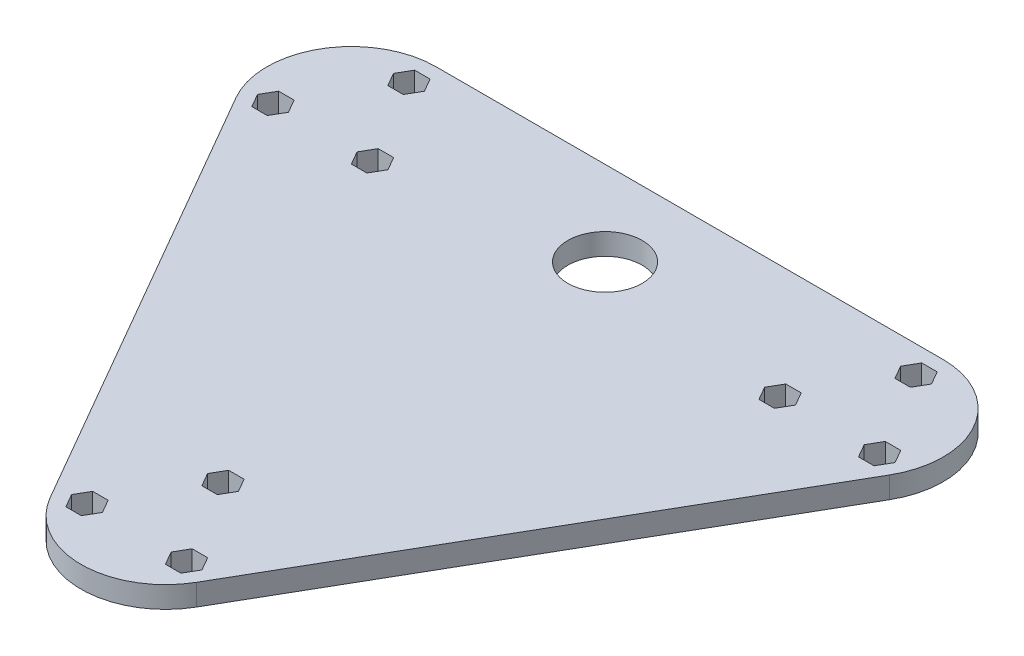
SolidWorks part; units mm, degrees
ref_plane "Plan de face" through (0, 0, 0) normal (0, 0, 1) x (1, 0, 0)
ref_plane "Plan de dessus" through (0, 0, 0) normal (0, 1, 0) x (1, 0, 0)
ref_plane "Plan de droite" through (0, 0, 0) normal (1, 0, 0) x (0, 0, -1)
sketch "Esquisse1" plane through (0, 0, 0) normal (0, 1, 0) x (1, 0, 0)
  line L0 (-96.6546, 52.5069) -> (-21.6546, -77.4931)
  line L1 (96.6546, 52.5069) -> (21.6546, -77.4931)
  line L2 (-75, 90) -> (75, 90)
  line L3 (-75, 65) -> (75, 65) construction
  arc A3 (-75, 90) -> (-96.6546, 52.5069) centre (-75, 65) ccw
  arc A4 (96.6546, 52.5069) -> (75, 90) centre (75, 65) ccw
  arc A5 (-21.6546, -77.4931) -> (21.6546, -77.4931) centre (0, -65) ccw
  circle A6 centre (0, 65) radius 11
  dimension "D1" = 22
  dimension "D6" = 50
  dimension "D2" = 65
  dimension "D3" = 65
  dimension "D4" = 150
  dimension "D5" = 75
extrude "Boss.-Extru.1" add sketch "Esquisse1" along normal blind 6.35
sketch "Esquisse3" plane through (0, 0, 0) normal (0, -1, 0) x (1, 0, 0)
  line L0 (75, -90) -> (-75, -90) construction
  line L1 (-79.5726, -82) -> (-77.2863, -85.96)
  line L2 (-77.2863, -85.96) -> (-72.7137, -85.96)
  line L3 (-72.7137, -85.96) -> (-70.4274, -82)
  line L4 (-70.4274, -82) -> (-72.7137, -78.04)
  line L5 (-72.7137, -78.04) -> (-77.2863, -78.04)
  line L6 (-77.2863, -78.04) -> (-79.5726, -82)
  line L7 (-94.295, -56.5) -> (-92.0087, -60.46)
  line L8 (-92.0087, -60.46) -> (-87.4361, -60.46)
  line L9 (-87.4361, -60.46) -> (-85.1498, -56.5)
  line L10 (-85.1498, -56.5) -> (-87.4361, -52.54)
  line L11 (-87.4361, -52.54) -> (-92.0087, -52.54)
  line L12 (-92.0087, -52.54) -> (-94.295, -56.5)
  line L13 (-64.8502, -56.5) -> (-62.5639, -60.46)
  line L14 (-62.5639, -60.46) -> (-57.9913, -60.46)
  line L15 (-57.9913, -60.46) -> (-55.705, -56.5)
  line L16 (-55.705, -56.5) -> (-57.9913, -52.54)
  line L17 (-57.9913, -52.54) -> (-62.5639, -52.54)
  line L18 (-62.5639, -52.54) -> (-64.8502, -56.5)
  line L19 (55.705, -56.5) -> (57.9913, -60.46)
  line L20 (57.9913, -60.46) -> (62.5639, -60.46)
  line L21 (62.5639, -60.46) -> (64.8502, -56.5)
  line L22 (64.8502, -56.5) -> (62.5639, -52.54)
  line L23 (62.5639, -52.54) -> (57.9913, -52.54)
  line L24 (57.9913, -52.54) -> (55.705, -56.5)
  line L25 (70.4274, -82) -> (72.7137, -85.96)
  line L26 (72.7137, -85.96) -> (77.2863, -85.96)
  line L27 (77.2863, -85.96) -> (79.5726, -82)
  line L28 (79.5726, -82) -> (77.2863, -78.04)
  line L29 (77.2863, -78.04) -> (72.7137, -78.04)
  line L30 (72.7137, -78.04) -> (70.4274, -82)
  line L31 (85.1498, -56.5) -> (87.4361, -60.46)
  line L32 (87.4361, -60.46) -> (92.0087, -60.46)
  line L33 (92.0087, -60.46) -> (94.295, -56.5)
  line L34 (94.295, -56.5) -> (92.0087, -52.54)
  line L35 (92.0087, -52.54) -> (87.4361, -52.54)
  line L36 (87.4361, -52.54) -> (85.1498, -56.5)
  line L37 (-4.5726, 48) -> (-2.2863, 44.04)
  line L38 (-2.2863, 44.04) -> (2.2863, 44.04)
  line L39 (2.2863, 44.04) -> (4.5726, 48)
  line L40 (4.5726, 48) -> (2.2863, 51.96)
  line L41 (2.2863, 51.96) -> (-2.2863, 51.96)
  line L42 (-2.2863, 51.96) -> (-4.5726, 48)
  line L43 (-19.295, 73.5) -> (-17.0087, 69.54)
  line L44 (-17.0087, 69.54) -> (-12.4361, 69.54)
  line L45 (-12.4361, 69.54) -> (-10.1498, 73.5)
  line L46 (-10.1498, 73.5) -> (-12.4361, 77.46)
  line L47 (-12.4361, 77.46) -> (-17.0087, 77.46)
  line L48 (-17.0087, 77.46) -> (-19.295, 73.5)
  line L49 (10.1498, 73.5) -> (12.4361, 69.54)
  line L50 (12.4361, 69.54) -> (17.0087, 69.54)
  line L51 (17.0087, 69.54) -> (19.295, 73.5)
  line L52 (19.295, 73.5) -> (17.0087, 77.46)
  line L53 (17.0087, 77.46) -> (12.4361, 77.46)
  line L54 (12.4361, 77.46) -> (10.1498, 73.5)
  circle A0 centre (-75, -82) radius 3.96 construction
  circle A1 centre (-89.7224, -56.5) radius 3.96 construction
  circle A2 centre (-60.2776, -56.5) radius 3.96 construction
  circle A3 centre (60.2776, -56.5) radius 3.96 construction
  circle A4 centre (75, -82) radius 3.96 construction
  circle A5 centre (89.7224, -56.5) radius 3.96 construction
  circle A6 centre (0, 48) radius 3.96 construction
  circle A7 centre (-14.7224, 73.5) radius 3.96 construction
  circle A8 centre (14.7224, 73.5) radius 3.96 construction
  dimension "D1" = 7.92
extrude "Enlèv. mat.-Extru.1" cut sketch "Esquisse3" against normal through all
